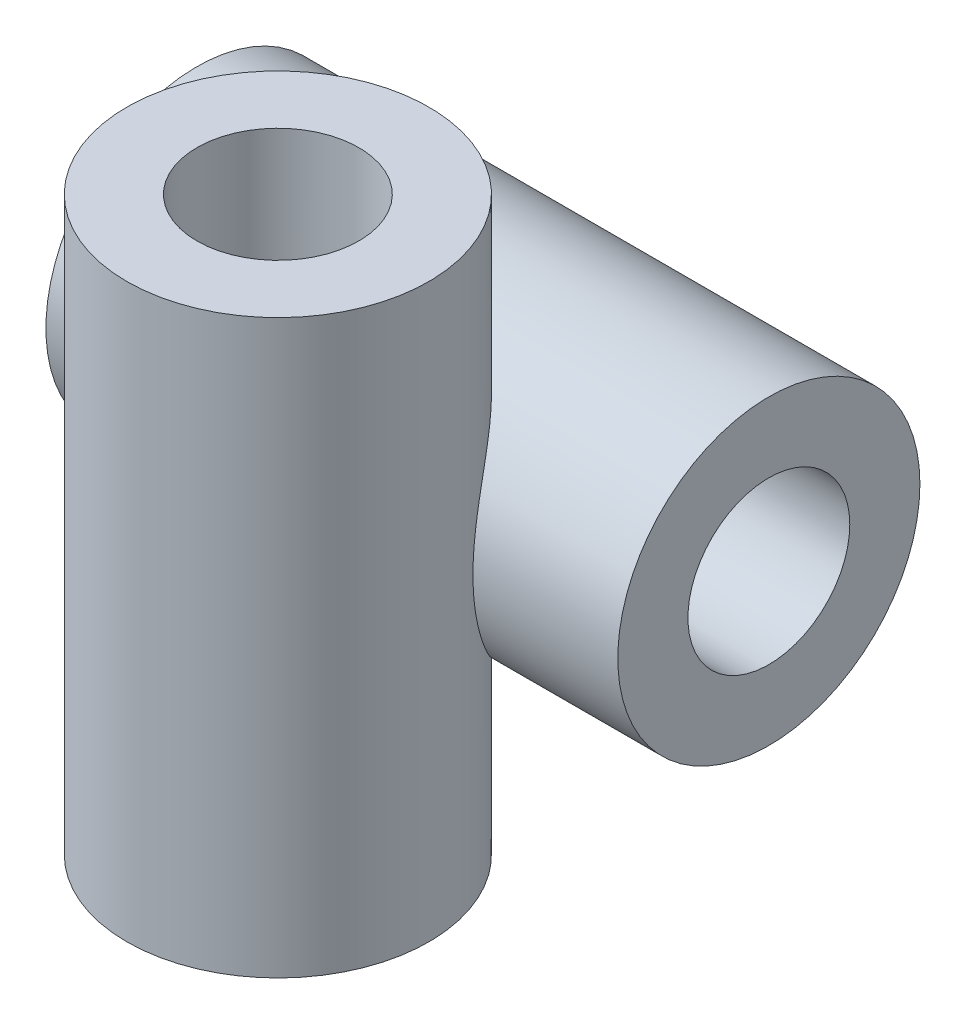
SolidWorks part; units mm, degrees
ref_plane "Front" through (0, 0, 0) normal (0, 0, 1) x (1, 0, 0)
ref_plane "Top" through (0, 0, 0) normal (0, 1, 0) x (1, 0, 0)
ref_plane "Right" through (0, 0, 0) normal (1, 0, 0) x (0, 0, -1)
sketch "Sketch1" plane through (0, 0, 0) normal (0, 1, 0) x (1, 0, 0)
  circle A0 centre (0, 0) radius 15
  circle A1 centre (0, 0) radius 28
  dimension "D1" = 30
  dimension "D2" = 56
extrude "Boss-Extrude1" add sketch "Sketch1" along normal blind 106
sketch "Sketch2" plane through (0, 106, 0) normal (0, 1, 0) x (1, 0, 0)
  circle A0 centre (0, 0) radius 28 construction
  point P0 (25.025, -12.5599)
sketch "Sketch4" plane through (0, 0, 0) normal (1, 0, 0) x (0, 0, -1)
  line L1 (28, 106) -> (-28, 106) construction
  circle A0 centre (38, 53) radius 28
  circle A1 centre (38, 53) radius 15
  dimension "D1" = 56
  dimension "D2" = 30
  dimension "D3" = 38
  dimension "D4" = 53
extrude "Boss-Extrude2" add sketch "Sketch4" along normal mid plane 106
sketch "Sketch5" plane through (53, 0, 0) normal (1, 0, 0) x (0, 0, -1)
  circle A0 centre (38, 53) radius 15 construction
  circle A1 centre (38, 53) radius 28
  circle A2 centre (38, 53) radius 28
  circle A3 centre (38, 53) radius 15
  dimension "D1" = 0
extrude "Cut-Extrude2" cut sketch "Sketch5" against normal blind 106 contours A3
scale "Scale1" scale about centroid uniform scaling yes scale factor 0.33
